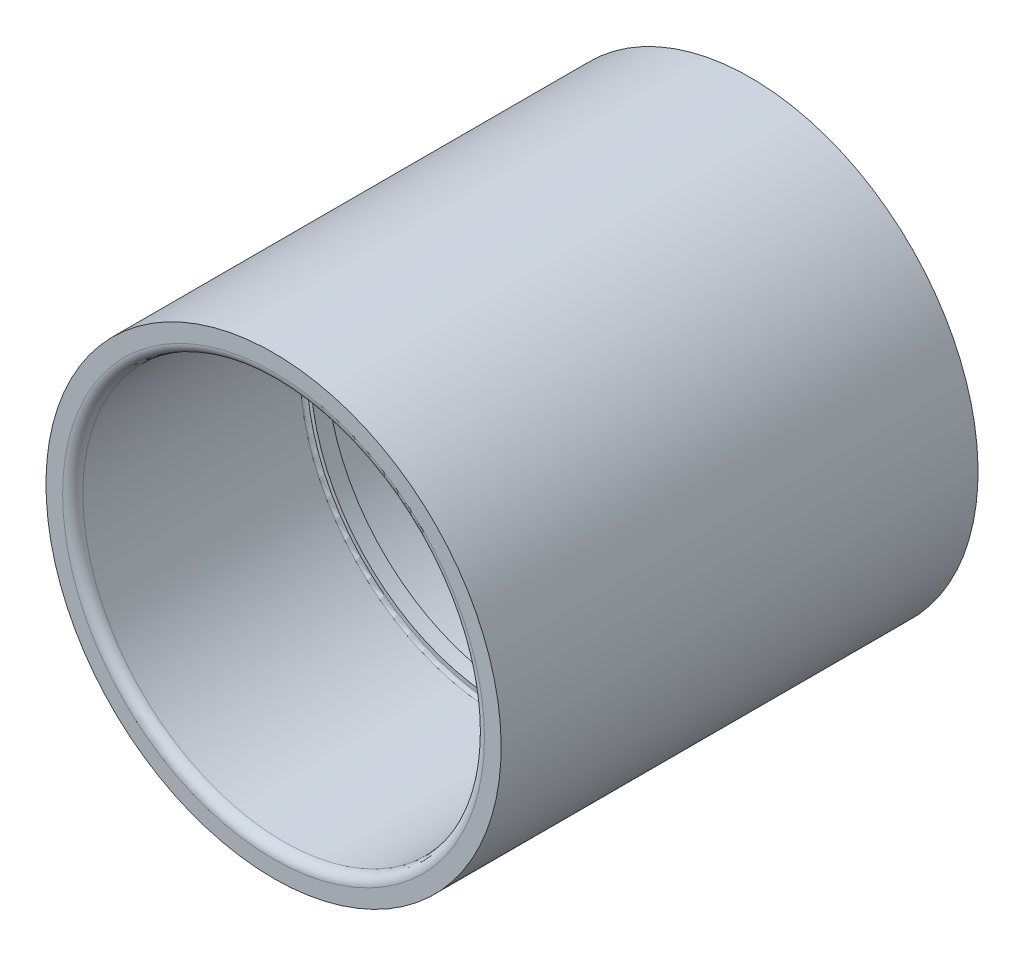
SolidWorks part; units mm, degrees
ref_plane "Front Plane" through (0, 0, 0) normal (0, 0, 1) x (1, 0, 0)
ref_plane "Top Plane" through (0, 0, 0) normal (0, 1, 0) x (1, 0, 0)
ref_plane "Right Plane" through (0, 0, 0) normal (1, 0, 0) x (0, 0, -1)
sketch "Sketch1" plane through (0, 0, 0) normal (0, 0, 1) x (1, 0, 0)
  circle A0 centre (0, 0) radius 34.3535 construction
  circle A1 centre (0, 0) radius 30.3149 construction
  circle A2 centre (0, 0) radius 29.1973 construction
  point P4 (-30.3149, 0)
  point P5 (0, 30.3149)
  point P6 (30.3149, 0)
  point P7 (0, -30.3149)
  point P9 (0, -29.1973)
  point P10 (0, -34.3535)
  dimension "Pipe OD" = 60.6298
  dimension "Max OD" = 68.707
  dimension "Thru ID" = 58.3946
sketch "Sketch2" plane through (0, 0, 0) normal (1, 0, 0) x (0, 0, -1)
  line L0 (-35.9918, 0) -> (35.9918, 0) construction
  point P3 (0, 0)
  dimension "OAL" = 71.9836
sketch "Sketch3" plane through (0, 0, 0) normal (1, 0, 0) x (0, 0, -1)
  line L0 (-35.9918, -34.3535) -> (35.9918, -34.3535)
  line L1 (-35.9918, -34.3535) -> (-35.9918, -30.3149)
  line L2 (-35.9918, -30.3149) -> (-1.1938, -30.3149)
  line L3 (-1.1938, -30.3149) -> (-1.1938, -29.1973)
  line L4 (35.9918, -34.3535) -> (35.9918, -30.3149)
  line L5 (35.9918, -30.3149) -> (1.1938, -30.3149)
  line L6 (1.1938, -30.3149) -> (1.1938, -29.1973)
  line L7 (-1.1938, -29.1973) -> (1.1938, -29.1973)
  line L9 (0, 34.3535) -> (0, -34.3535) construction
  line L10 (-35.9918, 0) -> (35.9918, 0) construction
  line L11 (-1.1938, -30.3149) -> (1.1938, -30.3149) construction
  point P11 (0, -29.1973)
  dimension "D1" = 34.3535
  dimension "D2" = 30.3149
  dimension "Socket Bottom Width" = 2.3876
  dimension "D3" = 29.1973
revolve "Revolve1" add sketch "Sketch3" angle 360 about L0
fillet "Fillet1" radius 1.524 2 edges at (0, -30.3149, -35.9918) (0, -30.3149, 35.9918)
fillet "Fillet2" radius 0.508 2 edges at (0, -30.3149, -1.1938) (0, -30.3149, 1.1938)
sketch "Sketch4" plane through (0, 0, 0) normal (1, 0, 0) x (0, 0, -1)
  line L0 (35.9918, -30.3149) -> (1.1938, -30.3149) construction
  line L1 (1.1938, -30.3149) -> (1.1938, -29.1973) construction
  line L2 (-1.1938, -29.1973) -> (1.1938, -29.1973) construction
  line L3 (-1.1938, -30.3149) -> (-1.1938, -29.1973) construction
  line L4 (-35.9918, -30.3149) -> (-1.1938, -30.3149) construction
  line L5 (34.4678, -30.3149) -> (1.7018, -30.3149)
  line L6 (1.1938, -29.8069) -> (1.1938, -29.1973)
  line L7 (-1.1938, -29.1973) -> (1.1938, -29.1973)
  line L8 (-1.1938, -29.8069) -> (-1.1938, -29.1973)
  line L9 (-34.4678, -30.3149) -> (-1.7018, -30.3149)
  line L10 (-35.9918, 0) -> (35.9918, 0) construction
  line L11 (-35.9918, 34.3535) -> (-35.9918, -34.3535) construction
  line L12 (35.9918, -34.3535) -> (35.9918, 34.3535) construction
  line L13 (34.4678, 30.3149) -> (1.7018, 30.3149)
  line L14 (1.1938, 29.8069) -> (1.1938, 29.1973)
  line L15 (-1.1938, 29.1973) -> (1.1938, 29.1973)
  line L16 (-1.1938, 29.8069) -> (-1.1938, 29.1973)
  line L17 (-34.4678, 30.3149) -> (-1.7018, 30.3149)
  line L18 (-35.9918, 31.8389) -> (-35.9918, 34.3535)
  line L19 (35.9918, 31.8389) -> (35.9918, 34.3535)
  line L20 (35.9918, -34.3535) -> (35.9918, -31.8389)
  line L21 (-35.9918, -31.8389) -> (-35.9918, -34.3535)
  arc A0 (1.7018, -30.3149) -> (1.1938, -29.8069) centre (1.7018, -29.8069) cw
  arc A1 (1.7018, 30.3149) -> (1.1938, 29.8069) centre (1.7018, 29.8069) ccw
  arc A2 (-1.7018, 30.3149) -> (-1.1938, 29.8069) centre (-1.7018, 29.8069) cw
  arc A3 (-1.7018, -30.3149) -> (-1.1938, -29.8069) centre (-1.7018, -29.8069) ccw
  arc A4 (-35.9918, -31.8389) -> (-34.4678, -30.3149) centre (-34.4678, -31.8389) cw
  arc A5 (35.9918, -31.8389) -> (34.4678, -30.3149) centre (34.4678, -31.8389) ccw
  arc A6 (35.9918, 31.8389) -> (34.4678, 30.3149) centre (34.4678, 31.8389) cw
  arc A7 (-34.4678, 30.3149) -> (-35.9918, 31.8389) centre (-34.4678, 31.8389) cw
  point P23 (1.1938, 30.3149)
  point P26 (-1.1938, 30.3149)
  point P46 (35.9918, 30.3149)
  point P49 (-35.9918, 30.3149)
  dimension "D1" = 0.508
  dimension "D2" = 1.524
equation "\"D1@Sketch3\"=\"Max OD@Sketch1\"/2"
equation "\"D2@Sketch3\"=\"Pipe OD@Sketch1\"/2"
equation "\"D3@Sketch3\"=\"Thru ID@Sketch1\"/2"
equation "\"D1@Sketch4\"=\"Socket Bottom Radius@Fillet2\""
equation "\"D2@Sketch4\"=\"ID Radius@Fillet1\""
